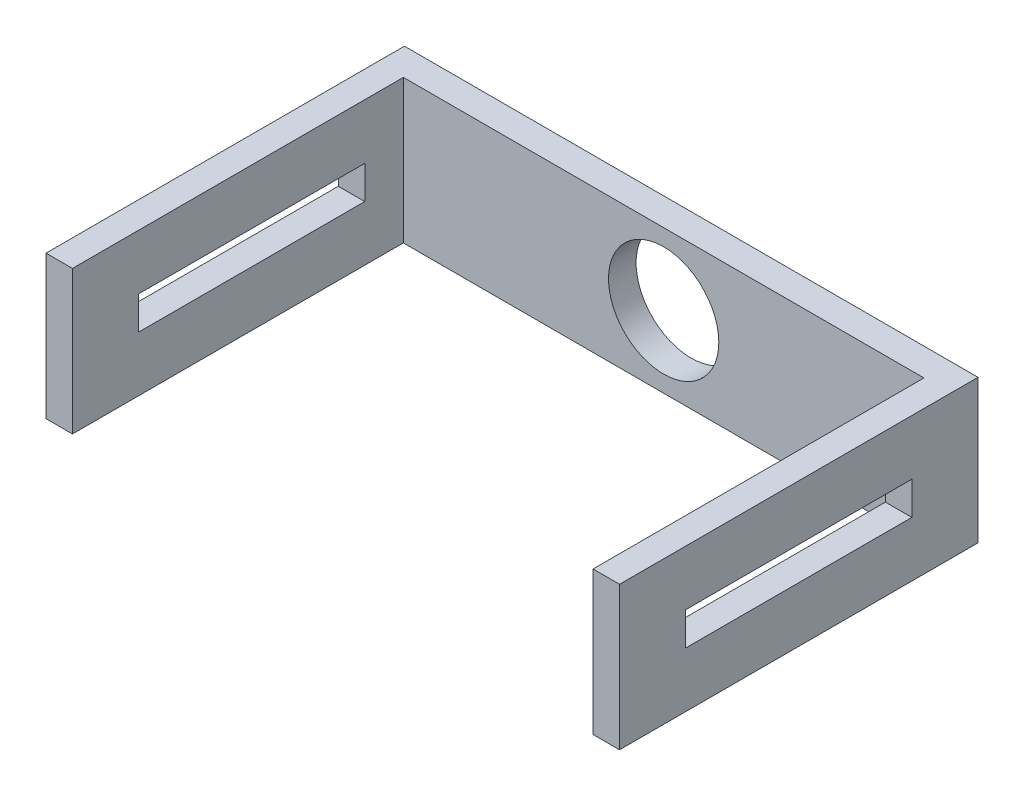
SolidWorks part; units mm, degrees
ref_plane "Front Plane" through (0, 0, 0) normal (0, 0, 1) x (1, 0, 0)
ref_plane "Top Plane" through (0, 0, 0) normal (0, 1, 0) x (1, 0, 0)
ref_plane "Right Plane" through (0, 0, 0) normal (1, 0, 0) x (0, 0, -1)
sketch "Sketch1" plane through (0, 0, 0) normal (0, 0, 1) x (1, 0, 0)
  line L1 (0, 0) -> (52, 0)
  line L2 (0, 0) -> (0, -13)
  line L3 (0, -13) -> (52, -13)
  line L4 (52, 0) -> (52, -13)
  dimension "D1" = 52
  dimension "D2" = 13
extrude "Boss-Extrude1" add sketch "Sketch1" along normal blind 2.5
sketch "Sketch2" plane through (0, 0, 2.5) normal (0, 0, 1) x (1, 0, 0)
  line L0 (0, -13) -> (52, -13) construction
  line L1 (0, 0) -> (2.4, 0)
  line L2 (0, 0) -> (0, -13)
  line L3 (0, -13) -> (2.4, -13)
  line L4 (2.4, 0) -> (2.4, -13)
  line L6 (52, 0) -> (49.6, 0)
  line L7 (52, 0) -> (52, -13)
  line L8 (52, -13) -> (49.6, -13)
  line L9 (49.6, 0) -> (49.6, -13)
  dimension "D1" = 2.4
  dimension "D2" = 2.4
extrude "Boss-Extrude2" add sketch "Sketch2" along normal blind 30
sketch "Sketch3" plane through (0, 0, 0) normal (-1, 0, 0) x (0, 0, 1)
  line L0 (0, 0) -> (0, -13) construction
  line L1 (6, -5) -> (26.5, -5)
  line L2 (6, -5) -> (6, -8)
  line L3 (6, -8) -> (26.5, -8)
  line L4 (26.5, -5) -> (26.5, -8)
  line L5 (32.5, 0) -> (0, 0) construction
  line L6 (32.5, -13) -> (0, -13) construction
  line L7 (32.5, 0) -> (32.5, -13) construction
  dimension "D1" = 6
  dimension "D2" = 5
  dimension "D3" = 5
  dimension "D4" = 6
extrude "Cut-Extrude1" cut sketch "Sketch3" against normal blind 55
sketch "Sketch4" plane through (0, 0, 2.5) normal (0, 0, 1) x (1, 0, 0)
  line L0 (0, 0) -> (0, -13) construction
  line L1 (49.6, 0) -> (2.4, 0) construction
  circle A0 centre (26, -6.5) radius 5
  dimension "D1" = 10
  dimension "D2" = 26
  dimension "D3" = 6.5
extrude "Cut-Extrude2" cut sketch "Sketch4" against normal blind 55
